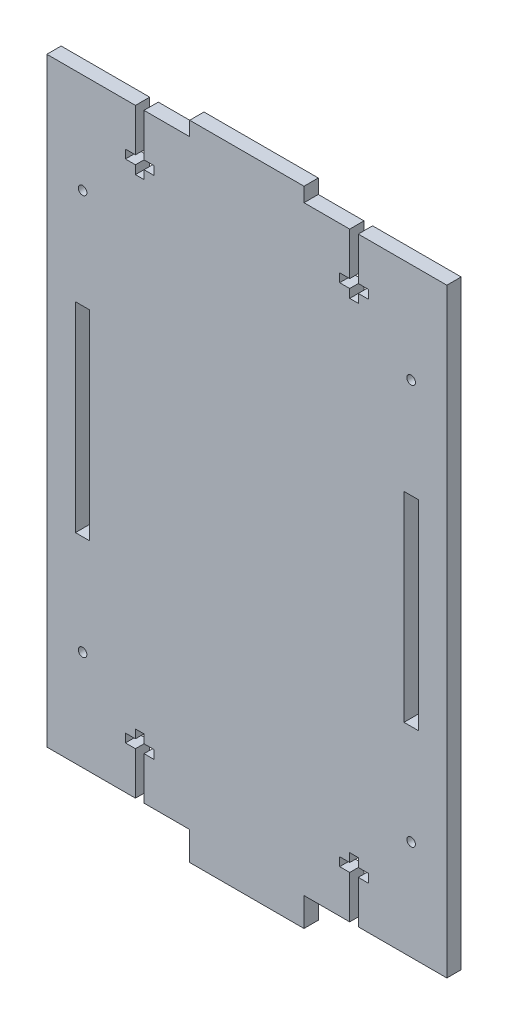
SolidWorks part; units mm, degrees
material "CA"
ref_plane "Alzado" through (0, 0, 0) normal (0, 0, 1) x (1, 0, 0)
ref_plane "Planta" through (0, 0, 0) normal (0, 1, 0) x (1, 0, 0)
ref_plane "Vista lateral" through (0, 0, 0) normal (1, 0, 0) x (0, 0, -1)
sketch "Croquis1" plane through (0, 0, 0) normal (0, 0, 1) x (1, 0, 0)
  line L0 (0, 0) -> (31, 0)
  line L1 (31, 0) -> (31, 15)
  line L2 (31, 15) -> (27.5, 15)
  line L3 (27.5, 15) -> (27.5, 18)
  line L4 (27.5, 18) -> (31, 18)
  line L5 (31, 18) -> (31, 21)
  line L6 (31, 21) -> (34, 21)
  line L7 (34, 21) -> (34, 18)
  line L8 (34, 18) -> (37.5, 18)
  line L9 (37.5, 18) -> (37.5, 15)
  line L10 (37.5, 15) -> (34, 15)
  line L11 (34, 15) -> (34, 0)
  line L12 (34, 0) -> (50, 0)
  line L13 (50, 0) -> (50, -10)
  line L14 (50, -10) -> (90, -10)
  line L15 (90, -10) -> (90, 0)
  line L16 (90, 0) -> (106, 0)
  line L17 (106, 0) -> (106, 15)
  line L18 (106, 15) -> (102.5, 15)
  line L19 (102.5, 15) -> (102.5, 18)
  line L20 (102.5, 18) -> (106, 18)
  line L21 (106, 18) -> (106, 21)
  line L22 (106, 21) -> (109, 21)
  line L23 (109, 21) -> (109, 18)
  line L24 (109, 18) -> (112.5, 18)
  line L25 (112.5, 18) -> (112.5, 15)
  line L26 (112.5, 15) -> (109, 15)
  line L27 (109, 15) -> (109, 0)
  line L28 (109, 0) -> (140, 0)
  line L29 (140, 0) -> (140, 210)
  line L31 (0, 0) -> (0, 210)
  line L32 (109, 210) -> (140, 210)
  line L33 (0, 210) -> (31, 210)
  line L34 (109, 195) -> (109, 210)
  line L35 (112.5, 195) -> (109, 195)
  line L36 (112.5, 192) -> (112.5, 195)
  line L37 (109, 192) -> (112.5, 192)
  line L38 (109, 189) -> (109, 192)
  line L39 (106, 189) -> (109, 189)
  line L40 (106, 192) -> (106, 189)
  line L41 (102.5, 192) -> (106, 192)
  line L42 (102.5, 195) -> (102.5, 192)
  line L43 (106, 195) -> (102.5, 195)
  line L44 (106, 210) -> (106, 195)
  line L45 (90, 210) -> (106, 210)
  line L46 (90, 215) -> (90, 210)
  line L47 (50, 215) -> (90, 215)
  line L48 (50, 210) -> (50, 215)
  line L49 (34, 210) -> (50, 210)
  line L50 (34, 195) -> (34, 210)
  line L51 (37.5, 195) -> (34, 195)
  line L52 (37.5, 192) -> (37.5, 195)
  line L53 (34, 192) -> (37.5, 192)
  line L54 (34, 189) -> (34, 192)
  line L55 (31, 189) -> (34, 189)
  line L56 (31, 192) -> (31, 189)
  line L57 (27.5, 192) -> (31, 192)
  line L58 (27.5, 195) -> (27.5, 192)
  line L59 (31, 195) -> (27.5, 195)
  line L60 (31, 210) -> (31, 195)
  line L61 (130, 140) -> (125, 140)
  line L62 (125, 140) -> (125, 70)
  line L63 (125, 70) -> (130, 70)
  line L64 (130, 70) -> (130, 140)
  line L65 (10, 140) -> (15, 140)
  line L66 (15, 70) -> (10, 70)
  line L67 (15, 140) -> (15, 70)
  line L68 (10, 70) -> (10, 140)
  circle A0 centre (12.5, 175) radius 1.5
  circle A1 centre (12.5, 35) radius 1.5
  circle A2 centre (127.5, 175) radius 1.5
  circle A3 centre (127.5, 35) radius 1.5
  point P67 (90, 212.5)
  dimension "D18" = 3
  dimension "D1" = 31
  dimension "D2" = 3.5
  dimension "D3" = 3
  dimension "D4" = 3
  dimension "D5" = 3.5
  dimension "D6" = 3.5
  dimension "D7" = 3
  dimension "D8" = 16
  dimension "D9" = 10
  dimension "D10" = 40
  dimension "D11" = 3
  dimension "D12" = 31
  dimension "D13" = 35
  dimension "D14" = 5
  dimension "D15" = 140
  dimension "D16" = 70
  dimension "D17" = 70
  dimension "D19" = 35
  dimension "D20" = 40
  dimension "D21" = 5
  dimension "D22" = 210
extrude "Saliente-Extruir1" add sketch "Croquis1" along normal blind 5 contours L31 L33 L60 L59 L58 L57 L56 L55 L54 L53 L52 L51 L50 L49 L48 L47 L46 L45 L44 L43 L42 L41 L40 L39 L38 L37 L36 L35 L34 L32 L29 L28 L27 L26 L25 L24 L23 L22 L21 L20 L19 L18 L17 L16 L15 L14 L13 L12 L11 L10 L9 L8 L7 L6 L5 L4 L3 L2 L1 L0 | L62 L63 L64 L61 | L68 L65 L67 L66 | A2 | A0 | A3 | A1
